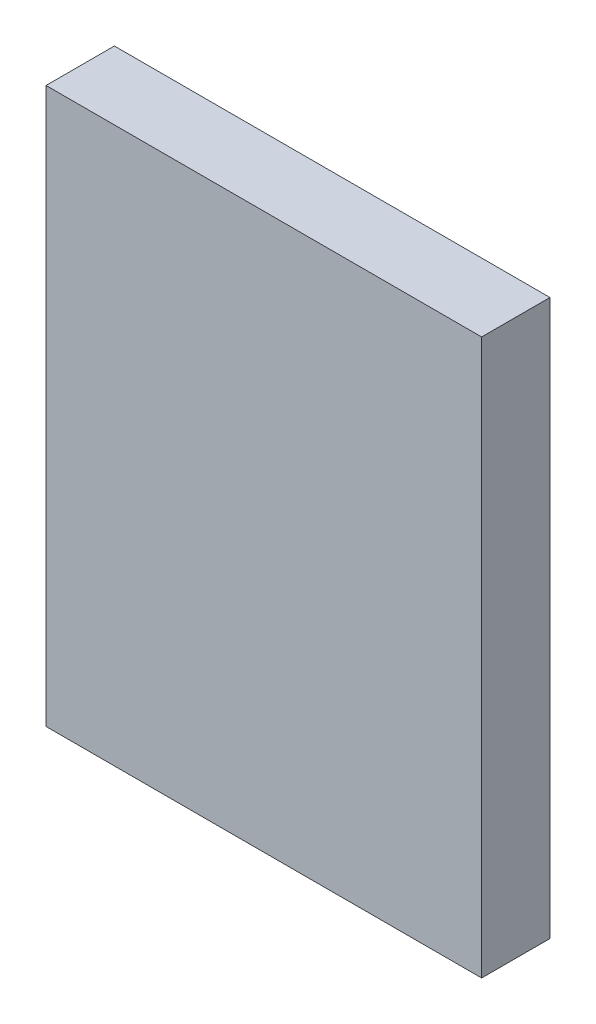
SolidWorks part; units mm, degrees
ref_plane "Plan de face" through (0, 0, 0) normal (0, 0, 1) x (1, 0, 0)
ref_plane "Plan de dessus" through (0, 0, 0) normal (0, 1, 0) x (1, 0, 0)
ref_plane "Plan de droite" through (0, 0, 0) normal (1, 0, 0) x (0, 0, -1)
sketch "Esquisse1" plane through (0, 0, 0) normal (0, 0, 1) x (1, 0, 0)
  line L1 (-25.8891, 19.5724) -> (25.1109, 19.5724)
  line L2 (-25.8891, 19.5724) -> (-25.8891, -45.4276)
  line L3 (-25.8891, -45.4276) -> (25.1109, -45.4276)
  line L4 (25.1109, 19.5724) -> (25.1109, -45.4276)
  dimension "D1" = 51
  dimension "D2" = 65
extrude "Boss.-Extru.1" add sketch "Esquisse1" along normal blind 8
